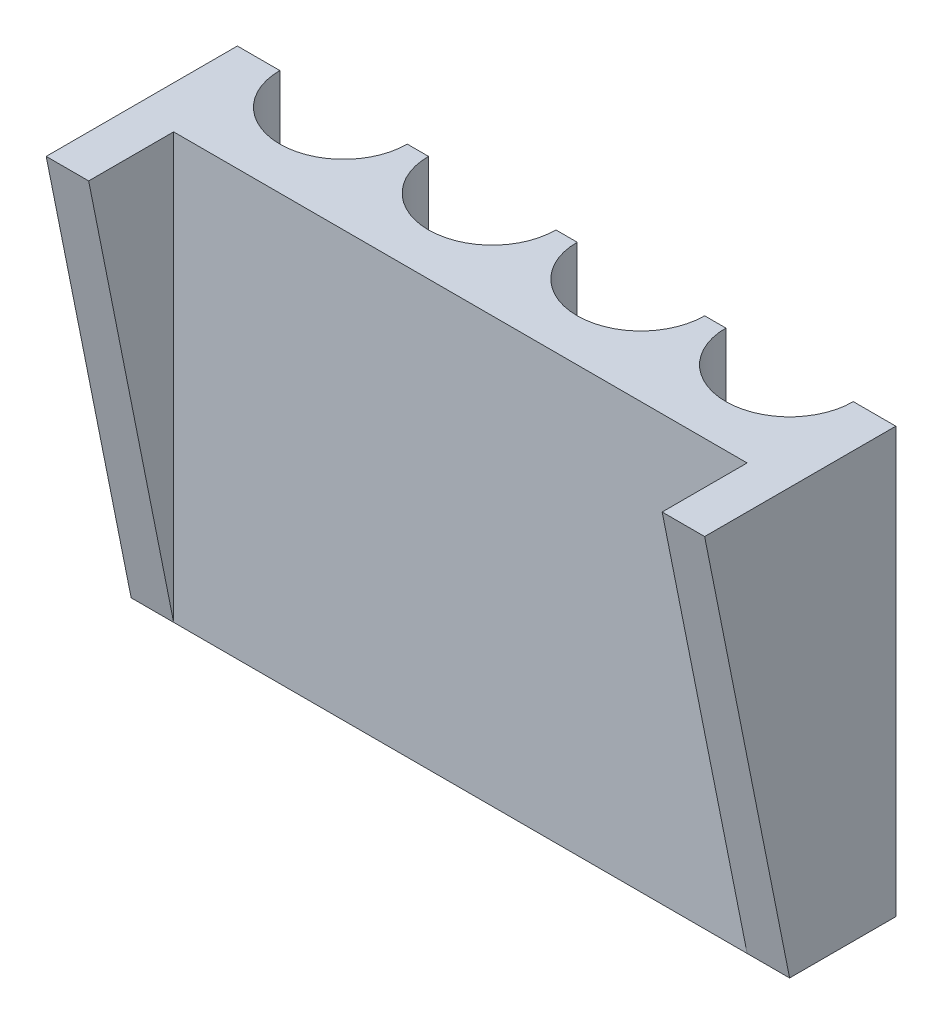
SolidWorks part; units mm, degrees
ref_plane "Front Plane" through (0, 0, 0) normal (0, 0, 1) x (1, 0, 0)
ref_plane "Top Plane" through (0, 0, 0) normal (0, 1, 0) x (1, 0, 0)
ref_plane "Right Plane" through (0, 0, 0) normal (1, 0, 0) x (0, 0, -1)
sketch "Sketch1" plane through (0, 0, 0) normal (0, 1, 0) x (1, 0, 0)
  line L1 (-77.5, 15) -> (77.5, 15)
  line L2 (-77.5, 15) -> (-77.5, -15)
  line L3 (-77.5, -15) -> (77.5, -15)
  line L4 (77.5, 15) -> (77.5, -15)
  line L5 (-77.5, 15) -> (77.5, -15) construction
  line L6 (-77.5, -15) -> (77.5, 15) construction
  point P0 (0, 0)
  dimension "D1" = 155
  dimension "D2" = 30
extrude "Boss-Extrude1" add sketch "Sketch1" along normal blind 100
sketch "Sketch2" plane through (0, 100, 0) normal (0, 1, 0) x (1, 0, 0)
  line L0 (77.5, 15) -> (-77.5, 15) construction
  circle A0 centre (-52.5, 15) radius 15
  circle A1 centre (-17.5, 15) radius 15
  circle A2 centre (17.5, 15) radius 15
  circle A3 centre (52.5, 15) radius 15
  dimension "D1" = 30
  dimension "D3" = 30
  dimension "D5" = 30
  dimension "D7" = 30
  dimension "D2" = 25
  dimension "D4" = 35
  dimension "D6" = 35
  dimension "D8" = 35
extrude "Cut-Extrude2" cut sketch "Sketch2" against normal blind 90
sketch "Sketch4" plane through (0, 0, 15) normal (0, 0, 1) x (1, 0, 0)
  line L1 (77.5, 100) -> (-77.5, 100)
  line L2 (77.5, 100) -> (77.5, 0)
  line L3 (77.5, 0) -> (-77.5, 0)
  line L4 (-77.5, 100) -> (-77.5, 0)
extrude "Cut-Extrude3" cut sketch "Sketch4" against normal blind 5
sketch "Sketch5" plane through (77.5, 0, 0) normal (1, 0, 0) x (0, 0, -1)
  line L0 (-10, 100) -> (-30, 100)
  line L1 (-30, 100) -> (-10, 0)
  line L2 (-10, 100) -> (-10, 0)
  dimension "D1" = 20
extrude "Boss-Extrude2" add sketch "Sketch5" against normal blind 155
sketch "Sketch6" plane through (0, 100, 0) normal (0, 1, 0) x (1, 0, 0)
  line L0 (-77.5, -30) -> (-77.5, -10) construction
  line L1 (-77.5, 15) -> (-77.5, -30) construction
  line L2 (-77.5, -10) -> (-67.5, -10) construction
  line L3 (77.5, -30) -> (77.5, -10) construction
  line L4 (77.5, -30) -> (77.5, 15) construction
  line L5 (77.5, -10) -> (67.5, -10) construction
  line L6 (-77.5, -30) -> (77.5, -30) construction
  line L7 (67.5, -10) -> (-67.5, -10)
  line L8 (67.5, -10) -> (67.5, -30)
  line L9 (67.5, -30) -> (-67.5, -30)
  line L10 (-67.5, -10) -> (-67.5, -30)
  dimension "D1" = 20
  dimension "D2" = 10
  dimension "D3" = 10
extrude "Cut-Extrude4" cut sketch "Sketch6" against normal blind 145
sketch "Sketch7" plane through (0, 0, -15) normal (0, 0, -1) x (-1, 0, 0)
  line L0 (-37.5, 10) -> (-37.5, 13) construction
  line L1 (-37.5, 100) -> (-37.5, 10) construction
  line L2 (-32.5, 10) -> (-32.5, 100) construction
  line L3 (-37.5, 13) -> (-32.5, 13)
  line L4 (-37.5, 13) -> (-37.5, 14)
  line L5 (-37.5, 14) -> (-32.5, 14)
  line L6 (-32.5, 13) -> (-32.5, 14)
  dimension "D1" = 3
  dimension "D2" = 1
extrude "Cut-Extrude6" cut sketch "Sketch7" against normal blind 1
sketch "Sketch8" plane through (32.5, 0, 0) normal (1, 0, 0) x (0, 0, -1)
  line L1 (14, 14) -> (15, 14)
  line L2 (14, 14) -> (14, 13)
  line L3 (14, 13) -> (15, 13)
  line L4 (15, 14) -> (15, 13)
extrude "Cut-Extrude7" cut sketch "Sketch8" against normal blind 71 and the other way blind 6
sketch "Sketch9" plane through (0, 0, -15) normal (0, 0, -1) x (-1, 0, 0)
  line L0 (-37.5, 14) -> (-37.5, 17) construction
  line L1 (-37.5, 100) -> (-37.5, 14) construction
  line L2 (-32.5, 14) -> (-32.5, 100) construction
  line L3 (-37.5, 17) -> (-32.5, 17)
  line L4 (-37.5, 17) -> (-37.5, 18)
  line L5 (-37.5, 18) -> (-32.5, 18)
  line L6 (-32.5, 17) -> (-32.5, 18)
  dimension "D1" = 3
  dimension "D2" = 1
extrude "Cut-Extrude8" cut sketch "Sketch9" against normal blind 1
sketch "Sketch10" plane through (32.5, 0, 0) normal (1, 0, 0) x (0, 0, -1)
  line L1 (14, 18) -> (15, 18)
  line L2 (14, 18) -> (14, 17)
  line L3 (14, 17) -> (15, 17)
  line L4 (15, 18) -> (15, 17)
extrude "Cut-Extrude9" cut sketch "Sketch10" against normal blind 71 and the other way blind 6
